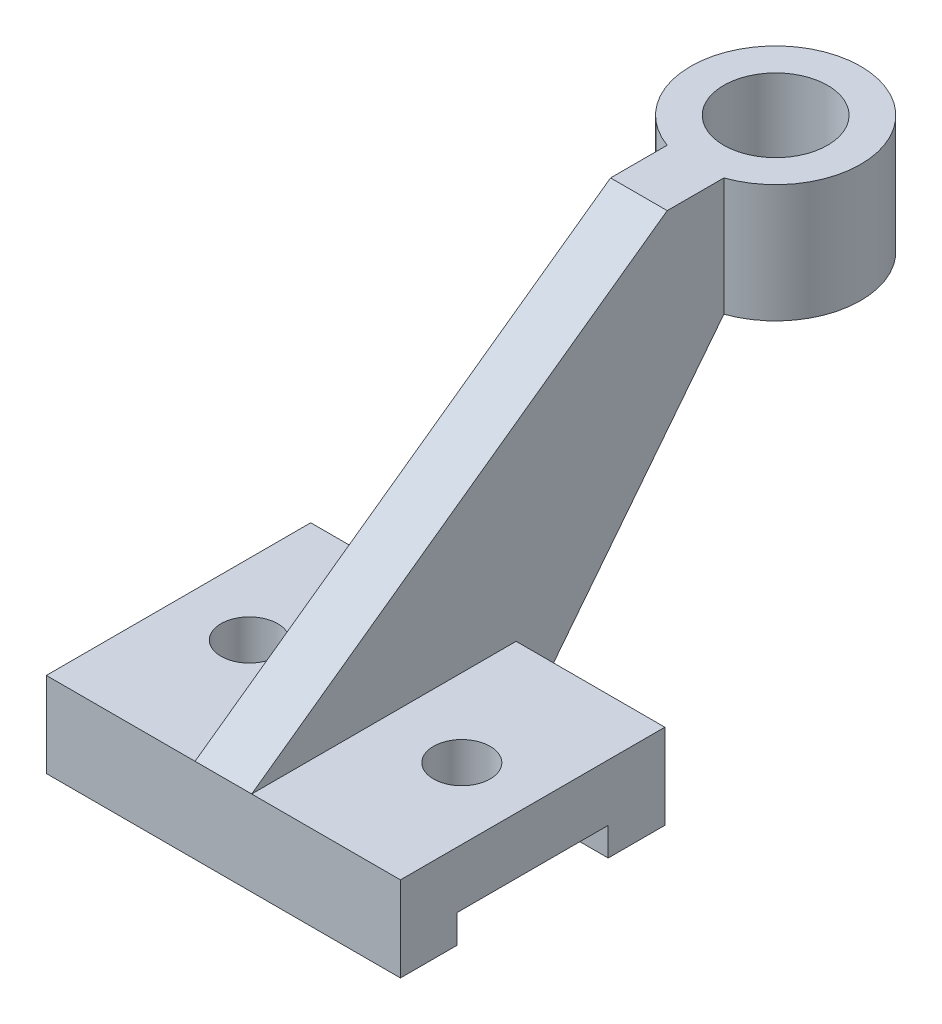
SolidWorks part; units mm, degrees
ref_plane "Front Plane" through (0, 0, 0) normal (0, 0, 1) x (1, 0, 0)
ref_plane "Top Plane" through (0, 0, 0) normal (0, 1, 0) x (1, 0, 0)
ref_plane "Right Plane" through (0, 0, 0) normal (1, 0, 0) x (0, 0, -1)
sketch "Sketch1" plane through (0, 0, 0) normal (1, 0, 0) x (0, 0, -1)
  line L0 (-22.4906, 0) -> (-22.4906, 18)
  line L1 (-22.4906, 18) -> (33.5094, 18)
  line L2 (33.5094, 18) -> (33.5094, 0)
  line L3 (33.5094, 0) -> (-22.4906, 0)
  dimension "D1" = 56
  dimension "D2" = 18
extrude "Boss-Extrude1" add sketch "Sketch1" against normal blind 75
sketch "Sketch2" plane through (0, 18, 0) normal (0, 1, 0) x (1, 0, 0)
  line L0 (0, 33.5094) -> (0, -22.4906) construction
  line L1 (-75, 33.5094) -> (-75, -22.4906) construction
  line L2 (-75, -22.4906) -> (0, -22.4906) construction
  circle A0 centre (-15, 5.5094) radius 6
  circle A1 centre (-60, 5.5094) radius 6
  dimension "D1" = 15
  dimension "D2" = 15
  dimension "D3" = 28
extrude "Cut-Extrude1" cut sketch "Sketch2" against normal blind 75
sketch "Sketch3" plane through (0, 0, 0) normal (1, 0, 0) x (0, 0, -1)
  line L0 (-10.4906, 0) -> (-10.4906, 6)
  line L1 (-22.4906, 0) -> (33.5094, 0) construction
  line L2 (-10.4906, 6) -> (21.5094, 6)
  line L3 (21.5094, 6) -> (21.5094, 0)
  line L4 (21.5094, 0) -> (-10.4906, 0)
  line L5 (33.5094, 0) -> (33.5094, 18) construction
  line L6 (-22.4906, 18) -> (-22.4906, 0) construction
  dimension "D1" = 6
  dimension "D2" = 12
  dimension "D3" = 12
extrude "Cut-Extrude2" cut sketch "Sketch3" against normal blind 75
move or copy body "Body-Move/Copy1" bodies to move or copy 103 copy no translate (37.5, 0, 0) parameters "D1"=37.5, "D2"=0, "D3"=0
sketch "Sketch4" plane through (0, 0, 0) normal (1, 0, 0) x (0, 0, -1)
  line L0 (-22.4906, 18) -> (65.5094, 81)
  line L2 (77.5094, 81) -> (77.5094, 56)
  line L3 (77.5094, 56) -> (33.5094, 0)
  line L4 (33.5094, 0) -> (33.5094, 18)
  line L5 (33.5094, 18) -> (-22.4906, 18)
  line L6 (65.5094, 81) -> (101.5094, 81)
  dimension "D1" = 25
  dimension "D2" = 12
  dimension "D3" = 36
  dimension "D4" = 63
  dimension "D5" = 100
extrude "Boss-Extrude5" add sketch "Sketch4" along normal mid plane 12 contours L6 L0 L5 L4 L3 L2
sketch "Sketch23" plane through (0, 81, 0) normal (0, 1, 0) x (1, 0, 0)
  circle A0 centre (0, 94.48) radius 18
  circle A1 centre (0, 94.48) radius 11
extrude "Boss-Extrude7" add sketch "Sketch23" against normal blind 25
sketch "Sketch5" plane through (0, 67.6533, 0) normal (0, 1, 0) x (1, 0, 0)
  line L0 (6, 45.5094) -> (-6, 45.5094) construction
  line L3 (-6, 45.5094) -> (6, 45.5094)
  line L4 (-6, 45.5094) -> (-6, 33.5094) construction
  line L5 (6, 33.5094) -> (-6, 33.5094) construction
  circle A0 centre (0, 69.5094) radius 24.7386
  circle A2 centre (0, 69.5094) radius 11
  dimension "D1" = 36
sketch "Sketch11" plane through (0, 21.2418, 18.8344) normal (0, 0.7482, 0.6634) x (1, 0, 0)
  line L0 (0, -4.8864) -> (0, 69.9564)
  line L1 (6, -4.8864) -> (-6, -4.8864) construction
  line L2 (6, 69.9564) -> (-6, 69.9564) construction
sketch "Sketch12" plane through (0, 67.6533, 0) normal (0, 1, 0) x (1, 0, 0)
  line L0 (0, 33.5094) -> (-0.126, 93.6865)
  circle A0 centre (-0.126, 69.5094) radius 24.177 construction
  circle A2 centre (-0.126, 69.5094) radius 11 construction
  dimension "D1" = 92
equation "\"37.5.00mm\"=0"
